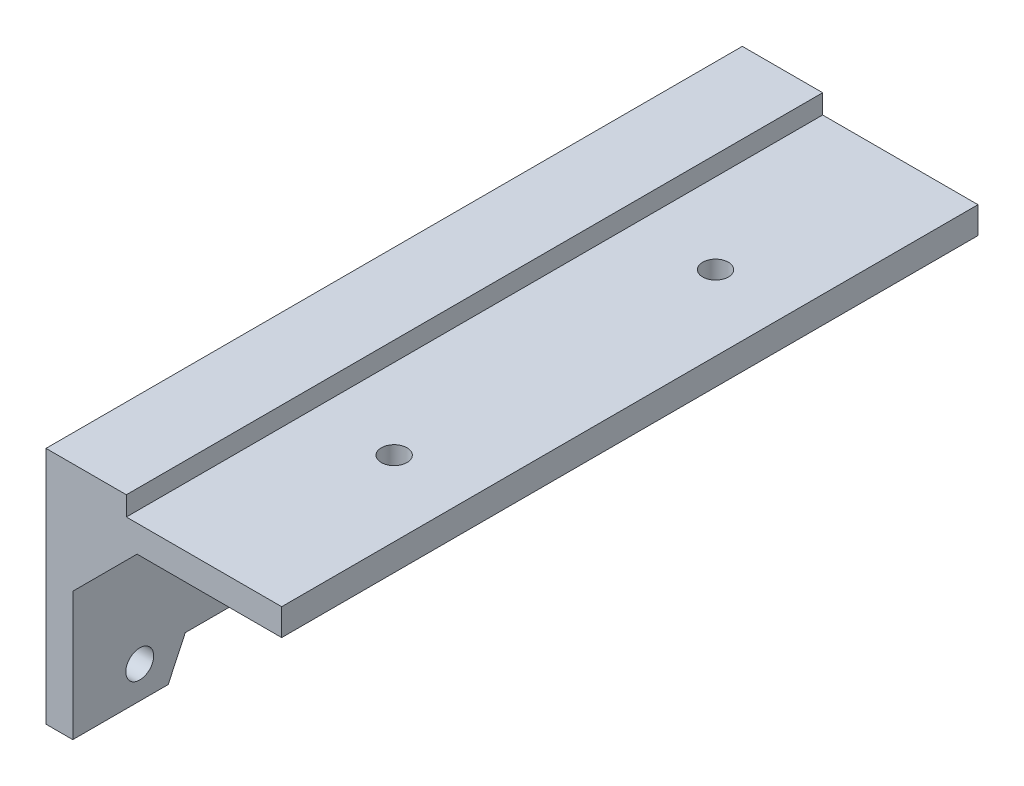
SolidWorks part; units mm, degrees
material "6061 Alloy"
ref_plane "Front Plane" through (0, 0, 0) normal (0, 0, 1) x (1, 0, 0)
ref_plane "Top Plane" through (0, 0, 0) normal (0, 1, 0) x (1, 0, 0)
ref_plane "Right Plane" through (0, 0, 0) normal (1, 0, 0) x (0, 0, -1)
sketch "Sketch1" plane through (0, 0, 0) normal (1, 0, 0) x (0, 0, -1)
  line L1 (-41.275, -13.335) -> (41.275, -13.335)
  line L2 (-41.275, -13.335) -> (-41.275, 13.335)
  line L3 (-41.275, 13.335) -> (41.275, 13.335)
  line L4 (41.275, -13.335) -> (41.275, 13.335)
  line L5 (0, 13.335) -> (0, -13.335) construction
  line L6 (-41.275, 0) -> (41.275, 0) construction
  point P0 (0, 0)
  dimension "D1" = 82.55
  dimension "D2" = 26.67
extrude "Boss-Extrude1" add sketch "Sketch1" along normal mid plane 3.175
sketch "Sketch2" plane through (-1.5875, 0, 0) normal (-1, 0, 0) x (0, 0, 1)
  line L0 (-33.3375, -5.715) -> (33.3375, -5.715) construction
  line L1 (41.275, -13.335) -> (-41.275, -13.335) construction
  line L2 (0, 13.335) -> (0, -13.335) construction
  line L3 (-41.275, 13.335) -> (41.275, 13.335) construction
  line L4 (-41.275, -13.335) -> (-41.275, 13.335) construction
  line L5 (41.275, 13.335) -> (41.275, -13.335) construction
  circle A0 centre (33.3375, -5.715) radius 1.651
  circle A1 centre (-33.3375, -5.715) radius 1.651
  circle A2 centre (-26.4795, -10.16) radius 1.5875
  circle A3 centre (26.4795, -10.16) radius 1.5875
  point P12 (0, -5.715)
  point P19 (0, -4.826)
  point P22 (0, -12.7)
  dimension "D1" = 66.675
  dimension "D2" = 7.9375
  dimension "D3" = 3.302
  dimension "D4" = 3.302
  dimension "D8" = 6.858
  dimension "D9" = 4.445
  dimension "D7" = 6.858
  dimension "D12" = 3.175
  dimension "D13" = 3.175
  dimension "D5" = 7.62
  dimension "D6" = 7.9375
  dimension "D10" = 7.62
  dimension "D11" = 4.445
extrude "Cut-Extrude1" cut sketch "Sketch2" against normal up to surface (3.175 mm away) up to face at (1.5875, 0, 0)
sketch "Sketch5" plane through (-1.5875, 0, 0) normal (-1, 0, 0) x (0, 0, 1)
  line L0 (0, 0) -> (0, 34.2734) construction
  line L3 (-41.275, 13.335) -> (41.275, 13.335) construction
  line L4 (-41.275, 16.51) -> (41.275, 16.51)
  line L5 (-41.275, 16.51) -> (-41.275, 13.335)
  line L6 (-41.275, 13.335) -> (41.275, 13.335)
  line L7 (41.275, 16.51) -> (41.275, 13.335)
  line L8 (0, 13.335) -> (0, 16.51) construction
  line L9 (-41.275, 14.9225) -> (41.275, 14.9225) construction
  point P2 (0, 14.9225)
  dimension "D1" = 3.175
  dimension "D2" = 82.55
extrude "Boss-Extrude3" add sketch "Sketch5" against normal blind 27.94
sketch "Sketch6" plane through (0, 16.51, 0) normal (0, 1, 0) x (1, 0, 0)
  line L0 (-1.5875, -41.275) -> (-1.5875, 41.275) construction
  line L1 (26.3525, -41.275) -> (-1.5875, -41.275) construction
  line L2 (26.3525, 41.275) -> (-1.5875, 41.275) construction
  circle A0 centre (17.4625, 19.05) radius 1.524
  circle A1 centre (17.4625, -19.05) radius 1.524
  dimension "D1" = 3.048
  dimension "D2" = 3.048
  dimension "D6" = 19.05
  dimension "D3" = 22.225
  dimension "D4" = 22.225
  dimension "D5" = 19.05
  dimension "D7" = 38.1
extrude "Cut-Extrude3" cut sketch "Sketch6" against normal up to surface (3.175 mm away) up to face at (13.97, 13.335, 0)
sketch "Sketch7" plane through (-1.5875, 0, 0) normal (-1, 0, 0) x (0, 0, 1)
  line L0 (0, 0) -> (0, -16.4603) construction
  line L1 (-31.75, -13.335) -> (31.75, -13.335)
  line L2 (41.275, -13.335) -> (-41.275, -13.335) construction
  line L3 (-27.94, -5.207) -> (27.94, -5.207)
  line L4 (-31.75, -13.335) -> (-27.94, -5.207)
  line L5 (27.94, -5.207) -> (31.75, -13.335)
  point P8 (0, -13.335)
  point P12 (0, -5.207)
  dimension "D1" = 63.5
  dimension "D2" = 55.88
  dimension "D3" = 3.81
  dimension "D4" = 3.81
  dimension "D5" = 8.128
extrude "Cut-Extrude4" cut sketch "Sketch7" against normal up to surface (3.175 mm away) up to face at (1.5875, -5.715, -31.6865)
sketch "Sketch8" plane through (0, 0, 41.275) normal (0, 0, 1) x (1, 0, 0)
  line L0 (1.5875, 13.335) -> (9.2075, 13.335)
  line L1 (26.3525, 13.335) -> (1.5875, 13.335) construction
  line L2 (1.5875, 5.715) -> (9.2075, 13.335)
  line L3 (1.5875, 13.335) -> (1.5875, -13.335) construction
  line L4 (1.5875, 5.715) -> (1.5875, 13.335)
  dimension "D1" = 7.62
  dimension "D2" = 7.62
extrude "Boss-Extrude4" add sketch "Sketch8" against normal up to surface (82.55 mm away) up to face at (8.7842, 5.5033, -41.275)
sketch "Sketch9" plane through (-1.5875, 0, 0) normal (-1, 0, 0) x (0, 0, 1)
  line L0 (-41.275, -13.335) -> (-41.275, -9.525)
  line L1 (-41.275, -13.335) -> (-41.275, 16.51) construction
  line L2 (-41.275, -9.525) -> (-29.9641, -9.525)
  line L3 (-27.94, -5.207) -> (-31.75, -13.335) construction
  line L4 (-29.9641, -9.525) -> (-31.75, -13.335)
  line L5 (-31.75, -13.335) -> (-41.275, -13.335)
  line L6 (41.275, -13.335) -> (41.275, -9.525)
  line L7 (41.275, 16.51) -> (41.275, -13.335) construction
  line L8 (41.275, -9.525) -> (29.9641, -9.525)
  line L9 (31.75, -13.335) -> (27.94, -5.207) construction
  line L10 (29.9641, -9.525) -> (31.75, -13.335)
  line L11 (31.75, -13.335) -> (41.275, -13.335)
  dimension "D1" = 3.81
  dimension "D2" = 3.81
extrude "Cut-Extrude5" cut sketch "Sketch9" against normal up to surface (3.175 mm away) up to face at (1.5875, -6.5405, 0)
sketch "Sketch10" plane through (0, 16.51, 0) normal (0, 1, 0) x (1, 0, 0)
  line L0 (26.3525, -41.275) -> (-1.5875, -41.275) construction
  line L1 (-1.5875, 41.275) -> (7.9375, 41.275)
  line L2 (-1.5875, 41.275) -> (-1.5875, -41.275)
  line L3 (-1.5875, -41.275) -> (7.9375, -41.275)
  line L4 (7.9375, 41.275) -> (7.9375, -41.275)
  dimension "D1" = 9.525
extrude "Boss-Extrude5" add sketch "Sketch10" along normal blind 2.286
